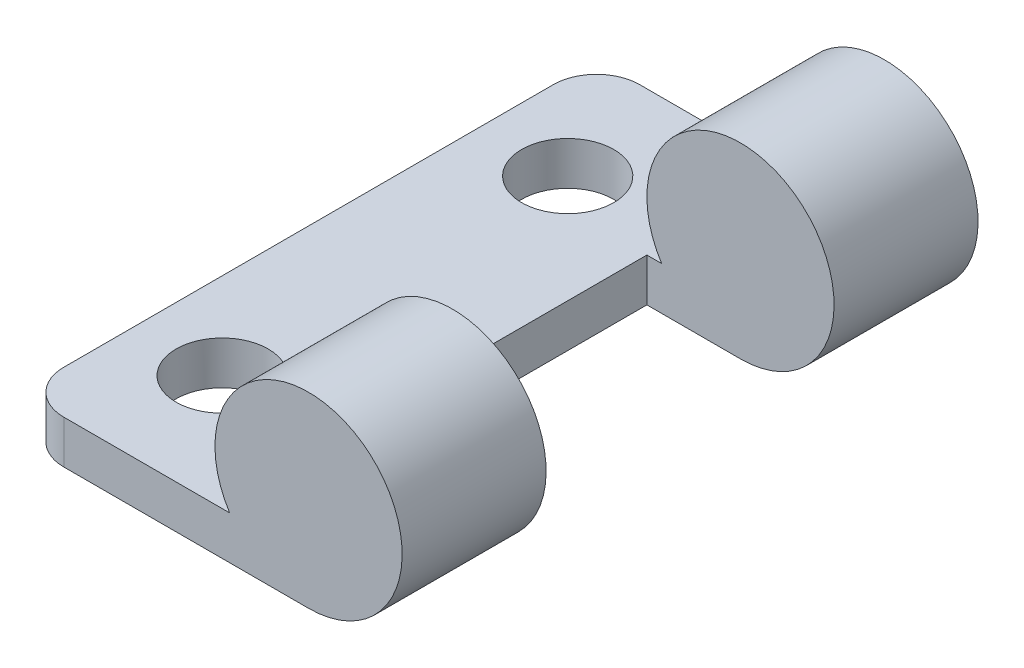
SolidWorks part; units mm, degrees
material "6061 合金"
ref_plane "前视基准面" through (0, 0, 0) normal (0, 0, 1) x (1, 0, 0)
ref_plane "上视基准面" through (0, 0, 0) normal (0, 1, 0) x (1, 0, 0)
ref_plane "右视基准面" through (0, 0, 0) normal (1, 0, 0) x (0, 0, -1)
sketch "草图1" plane through (0, 0, 0) normal (0, 0, 1) x (1, 0, 0)
  line L0 (0, -3.25) -> (-10, -3.25)
  line L1 (-10, -3.25) -> (-10, -1.75)
  line L2 (-10, -1.75) -> (-2.7386, -1.75)
  arc A0 (0, -3.25) -> (-2.7386, -1.75) centre (0, 0) ccw
  dimension "D1" = 6.5
  dimension "D2" = 10
  dimension "D3" = 1.5
extrude "凸台-拉伸1" add sketch "草图1" along normal mid plane 20
sketch "草图2" plane through (0, -1.75, 0) normal (0, 1, 0) x (1, 0, 0)
  line L0 (0, 0) -> (-24.3285, 0) construction
  line L1 (-3.25, 10) -> (-3.25, -10) construction
  line L2 (3.25, 5) -> (-3.25, 5)
  line L3 (3.25, 5) -> (3.25, -5)
  line L4 (3.25, -5) -> (-3.25, -5)
  line L5 (-3.25, 5) -> (-3.25, -5)
  line L6 (0, -5) -> (0, 5) construction
  line L7 (3.25, 0) -> (-3.25, 0) construction
  circle A0 centre (-7, -6) radius 1.6
  circle A1 centre (-7, 6) radius 1.6
  dimension "D1" = 7
  dimension "D2" = 12
  dimension "D3" = 3.2
  dimension "D4" = 10
extrude "切除-拉伸1" cut sketch "草图2" against normal through all both and the other way through all
fillet "圆角1" radius 1.5 2 edges at (-10, -2.5, -10) (-10, -2.5, 10)
